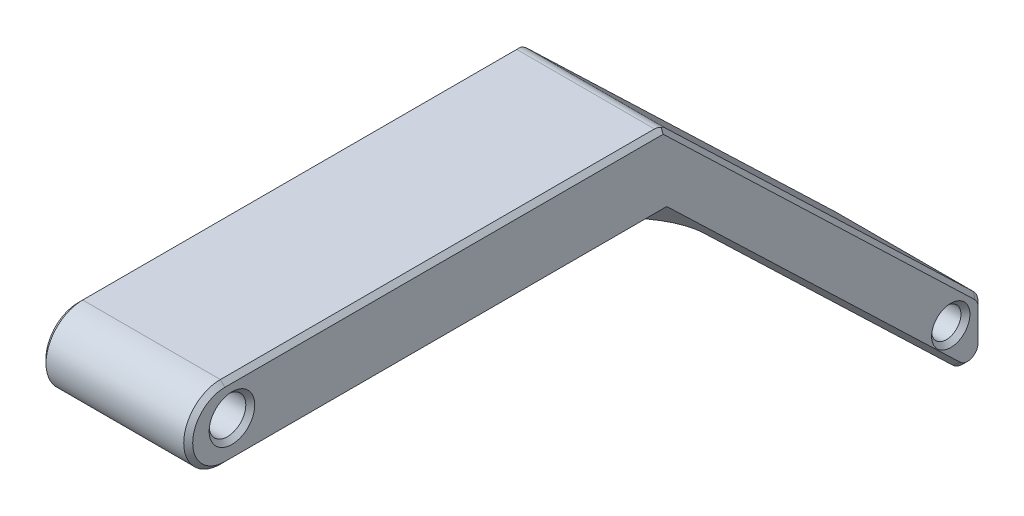
SolidWorks part; units mm, degrees
ref_plane "前视基准面" through (0, 0, 0) normal (0, 0, 1) x (1, 0, 0)
ref_plane "上视基准面" through (0, 0, 0) normal (0, 1, 0) x (1, 0, 0)
ref_plane "右视基准面" through (0, 0, 0) normal (1, 0, 0) x (0, 0, -1)
other "Configuration Table"
sketch "草图1" plane through (0, 0, 0) normal (1, 0, 0) x (0, 0, -1)
  line L1 (-13.1742, 5.6744) -> (-1.1742, 5.6744)
  line L2 (-13.1742, 5.6744) -> (-13.1742, 3.6744)
  line L3 (-13.1742, 3.6744) -> (-1.1742, 3.6744)
  line L4 (-1.1742, 5.6744) -> (-1.1742, 3.6744)
  line L5 (-13.1742, 5.6744) -> (-1.1742, 3.6744) construction
  line L6 (-13.1742, 3.6744) -> (-1.1742, 5.6744) construction
  point P0 (-7.1742, 4.6744)
  dimension "D1" = 12
  dimension "D2" = 2
extrude "凸台-拉伸1" add sketch "草图1" along normal blind 4
sketch "草图3" plane through (4, 0, 0) normal (1, 0, 0) x (0, 0, -1)
  line L3 (8.0183, 12.3878) -> (8.0183, 13.3878)
sketch "草图4" plane through (4, 0, 0) normal (1, 0, 0) x (0, 0, -1)
  line L0 (-1.1742, 5.6744) -> (-1.1742, 3.6744)
  line L1 (-1.1742, 5.6744) -> (7.4847, -2.6336)
  line L2 (-1.1742, 3.6744) -> (7.4847, -4.6336)
  line L3 (7.4847, -2.6336) -> (7.4847, -4.6336)
  point P0 (7.4847, -4.6336)
  dimension "D1" = 12
extrude "凸台-拉伸2" add sketch "草图4" against normal blind 4
sketch "草图7" plane through (4, 0, 0) normal (1, 0, 0) x (0, 0, -1)
  line L0 (-13.1742, 5.6744) -> (-13.1742, 3.6744)
  arc A0 (-13.1742, 3.6744) -> (-13.1742, 5.6744) centre (-13.1742, 4.6744) cw
extrude "凸台-拉伸4" add sketch "草图7" against normal up to vertex (4 mm away)
sketch "草图8" plane through (4, 0, 0) normal (1, 0, 0) x (0, 0, -1)
  circle A0 centre (-12.9815, 4.7279) radius 0.5
  dimension "D1" = 1
extrude "切除-拉伸1" cut sketch "草图8" against normal blind 10
sketch "草图9" plane through (4, 0, 0) normal (1, 0, 0) x (0, 0, -1)
  circle A0 centre (6.6195, -2.883) radius 0.4
  point P2 (6.729, -2.9309)
  point P3 (6.6195, -2.883)
  point P4 (6.5895, -3.4005)
  dimension "D1" = 0.8
extrude "切除-拉伸2" cut sketch "草图9" against normal blind 10
scale "缩放比例1" scale about centroid uniform scaling yes scale factor 2.454545
fillet "圆角1" radius 1 2 edges at (2, -10.8795, -22.988) (2, -15.7886, -22.988)
chamfer "倒角1" distance 0.3 angle 45 18 edges at (6.9091, -14.3631, -22.3802) (-2.9091, -4.7805, -11.5149) (6.9091, -4.7805, -11.5149) (6.9091, 4.6038, 12.9931) (6.9091, 7.0583, 30.1749) (-2.9091, 7.0583, 30.1749) (6.9091, 9.5129, 12.9931) (6.9091, -0.5357, -12.2073) (-2.9091, -0.5357, -12.2073) (6.9091, -10.9136, -22.9079) (-2.9091, -12.3745, -22.988) (6.9091, -12.3745, -22.988) (6.9091, 7.1897, 26.0201) (6.9091, -11.4916, -21.8461) (-2.9091, -10.9136, -22.9079) (-2.9091, 9.5129, 12.9931) (-2.9091, -14.3631, -22.3802) (-2.9091, 4.6038, 12.9931)
fillet "圆角2" radius 1 1 edges at (2, 9.5129, -1.7342)
fillet "圆角3" radius 10 1 edges at (2, 4.6038, -1.7342)
